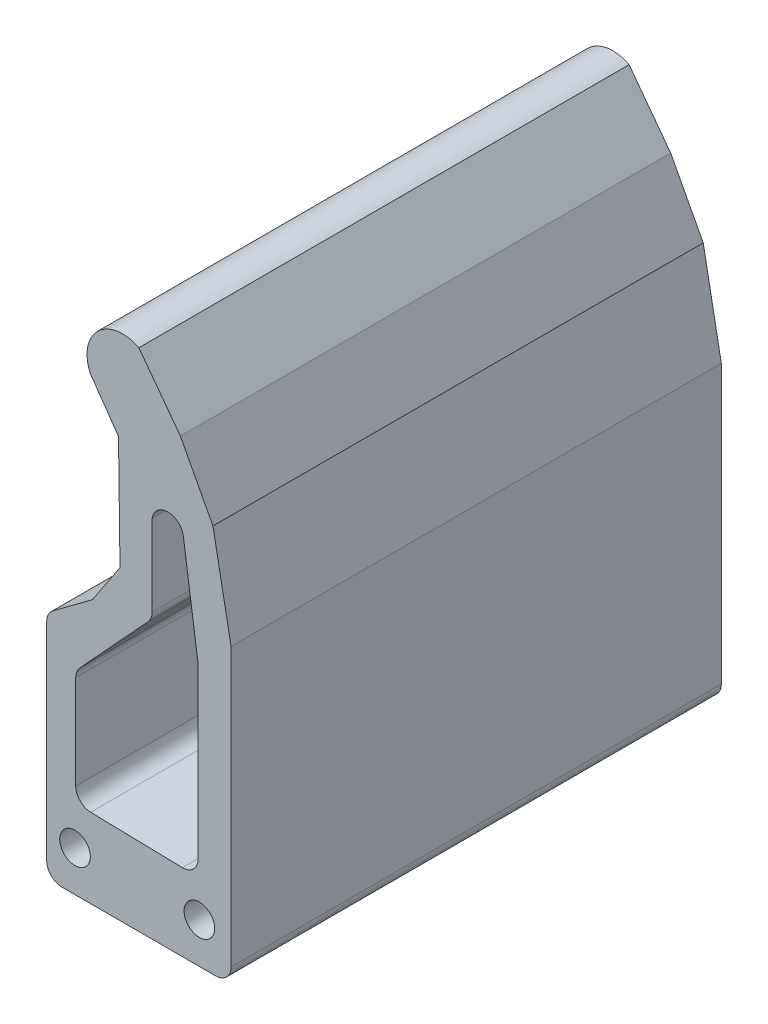
SolidWorks part; units mm, degrees
ref_plane "Front Plane" through (0, 0, 0) normal (0, 0, 1) x (1, 0, 0)
ref_plane "Top Plane" through (0, 0, 0) normal (0, 1, 0) x (1, 0, 0)
ref_plane "Right Plane" through (0, 0, 0) normal (1, 0, 0) x (0, 0, -1)
other "Graphic1"
ref_plane "Plane1" through (0, 0, 40) normal (0, 0, 1) x (1, 0, 0)
sketch "Sketch1" plane through (0, 0, 40) normal (0, 0, 1) x (1, 0, 0)
  line L0 (-312.0305, 377.8685) -> (-310.1939, 375.2448)
  line L1 (-310.1939, 375.2448) -> (-310.096, 367.8752)
  line L2 (-310.096, 367.8752) -> (-311.8891, 365.1664)
  line L3 (-311.8891, 365.1664) -> (-314.8817, 362.9367)
  line L4 (-314.8817, 362.9367) -> (-314.8817, 347.9184)
  line L5 (-314.8817, 347.9184) -> (-302.8474, 347.9184)
  line L6 (-302.8474, 347.9184) -> (-302.8474, 367.0456)
  line L7 (-302.8474, 367.0456) -> (-304.0281, 373.2638)
  line L8 (-304.0281, 373.2638) -> (-306.1533, 377.2782)
  line L9 (-306.1533, 377.2782) -> (-308.8645, 380.917)
  line L10 (-312.9884, 360.5984) -> (-312.9884, 353.11)
  line L11 (-312.9884, 353.11) -> (-305, 352.9273)
  line L12 (-305, 352.9273) -> (-305, 365)
  line L13 (-305, 365) -> (-305.9529, 371.67)
  line L14 (-312.9884, 360.5984) -> (-307.9946, 366.0233)
  line L15 (-307.9946, 366.0233) -> (-307.9946, 371.7027)
  arc A0 (-312.0305, 377.8685) -> (-308.8645, 380.917) centre (-309.9244, 378.8495) cw
  arc A1 (-307.9946, 371.7027) -> (-305.9529, 371.67) centre (-306.9758, 371.5556) cw
  point P22 (-312.9884, 353.11)
  point P26 (-305, 352.9273)
extrude "Boss-Extrude1" add sketch "Sketch1" along normal blind 32
fillet "Fillet1" radius 1 7 edges at (-314.8817, 347.9184, 56) (-305, 352.9273, 56) (-302.8474, 347.9184, 56) (-312.9884, 353.11, 56) (-314.8817, 362.9367, 56) (-312.9884, 360.5984, 56) (-307.9946, 366.0233, 56)
sketch "Sketch2" plane through (0, 0, 72) normal (0, 0, 1) x (1, 0, 0)
  circle A0 centre (-313.0311, 350.5603) radius 1
  circle A1 centre (-304.9145, 350.5603) radius 1
extrude "Cut-Extrude1" cut sketch "Sketch2" against normal blind 32
